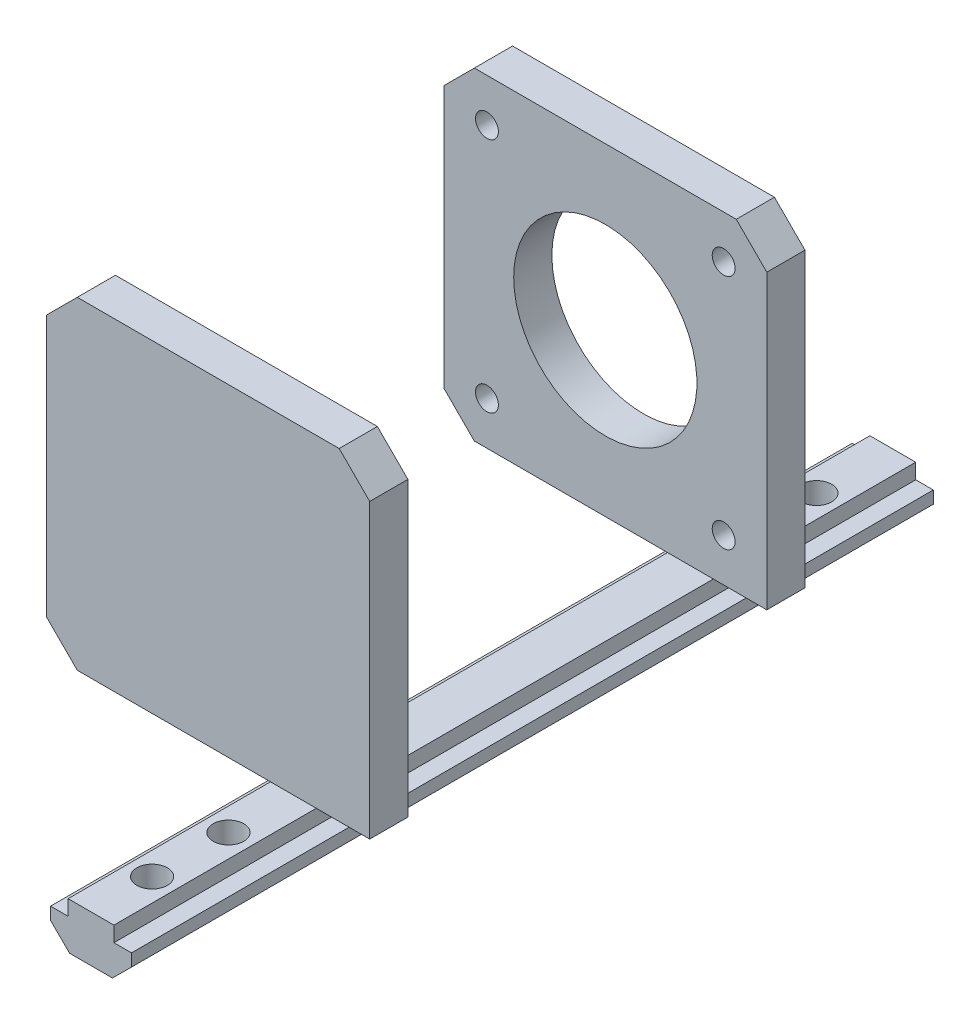
SolidWorks part; units mm, degrees
ref_plane "Front (XY)" through (0, 0, 0) normal (0, 0, 1) x (1, 0, 0)
ref_plane "Top (XZ)" through (0, 0, 0) normal (0, 1, 0) x (1, 0, 0)
ref_plane "Right (YZ)" through (0, 0, 0) normal (1, 0, 0) x (0, 0, -1)
sketch "Sketch1" plane through (0, 0, 0) normal (0, 0, 1) x (1, 0, 0)
  line L0 (0, -6.1) -> (0, 0) construction
  line L1 (-3, 0) -> (3, 0)
  line L2 (-3, 0) -> (-3, -2)
  line L3 (3, 0) -> (3, -2)
  line L4 (-3, -2) -> (-5.3, -2)
  line L5 (3, -2) -> (5.3, -2)
  line L6 (-5.3, -2) -> (-5.3, -3.62)
  line L7 (5.3, -2) -> (5.3, -3.62)
  line L8 (-2.8, -6.1) -> (2.8, -6.1)
  line L9 (-2.8, -6.1) -> (-5.3, -3.62)
  line L10 (2.8, -6.1) -> (5.3, -3.62)
  point P4 (0, 0)
  point P13 (0, -6.1)
  dimension "D1" = 6
  dimension "D2" = 6.1
  dimension "D3" = 2.3
  dimension "D4" = 4.1
  dimension "D5" = 3.5214
  dimension "D6" = 1.62
extrude "Boss-Extrude1" add sketch "Sketch1" along normal mid plane 57
sketch "Sketch2" plane through (0, 0, -28.5) normal (0, 0, -1) x (-1, 0, 0)
  line L3 (32.3, 0) -> (32.3, 42.3)
  line L4 (32.3, 42.3) -> (-10, 42.3)
  line L5 (-10, 42.3) -> (-10, 0)
  line L8 (0, 0) -> (-10, 0)
  line L9 (0, 0) -> (32.3, 0)
  dimension "D1" = 42.3
  dimension "D2" = 10
  dimension "D3" = 32.3
extrude "Boss-Extrude2" add sketch "Sketch2" against normal blind 5
chamfer "Chamfer1" distance 4 angle 45 3 edges at (10, 42.3, -26) (-32.3, 42.3, -26) (-32.3, 0, -26)
pattern_linear "LPattern1" count 2 spacing 52 along (0, 0, 1) of "Boss-Extrude2", "Chamfer1"
sketch "Sketch4" plane through (0, 0, -28.5) normal (0, 0, -1) x (-1, 0, 0)
  line L0 (-10, 0) -> (30.3, 40.3) construction
  line L1 (32.3, 38.3) -> (28.3, 42.3) construction
  line L2 (30.3, 2) -> (-8, 40.3) construction
  line L3 (28.3, 0) -> (32.3, 4) construction
  line L4 (-6, 42.3) -> (-10, 38.3) construction
  circle A0 centre (11.15, 21.15) radius 12
  circle A1 centre (26.65, 36.65) radius 1.5
  circle A2 centre (-4.35, 36.65) radius 1.5
  circle A3 centre (-4.35, 5.65) radius 1.5
  circle A4 centre (26.65, 5.65) radius 1.5
  dimension "D1" = 24
  dimension "D2" = 31
  dimension "D6" = 3
  dimension "D3" = 31
  dimension "D4" = 15.5
  dimension "D5" = 15.5
extrude "Cut-Extrude1" cut sketch "Sketch4" against normal up to next
sketch "Sketch5" plane through (0, 0, 0) normal (0, 0, 1) x (1, 0, 0)
  line L0 (-3, -2) -> (-5.3, -2) construction
  line L1 (-5.3, -2) -> (-5.3, -3.62) construction
  line L2 (-5.3, -3.62) -> (-2.8, -6.1) construction
  line L3 (-2.8, -6.1) -> (2.8, -6.1) construction
  line L4 (2.8, -6.1) -> (5.3, -3.62) construction
  line L5 (5.3, -3.62) -> (5.3, -2) construction
  line L6 (5.3, -2) -> (3, -2) construction
  line L7 (3, -2) -> (3, 0) construction
  line L8 (-3, 0) -> (-3, -2) construction
  line L9 (-3, -2) -> (-5.3, -2)
  line L10 (-5.3, -2) -> (-5.3, -3.62)
  line L11 (-5.3, -3.62) -> (-2.8, -6.1)
  line L12 (-2.8, -6.1) -> (2.8, -6.1)
  line L13 (2.8, -6.1) -> (5.3, -3.62)
  line L14 (5.3, -3.62) -> (5.3, -2)
  line L15 (5.3, -2) -> (3, -2)
  line L16 (3, -2) -> (3, 0)
  line L17 (-3, 0) -> (-3, -2)
  line L18 (-3, 0) -> (3, 0)
extrude "Boss-Extrude3" add sketch "Sketch5" against normal blind 50 and the other way blind 55
sketch "Sketch6" plane through (0, 0, 0) normal (0, 1, 0) x (1, 0, 0)
  circle A0 centre (0, 40) radius 2
  circle A1 centre (0, -37) radius 2
  circle A2 centre (0, -47) radius 2
  dimension "D1" = 4
  dimension "D2" = 40
  dimension "D4" = 10
  dimension "D3" = 37
extrude "Cut-Extrude2" cut sketch "Sketch6" against normal through all
